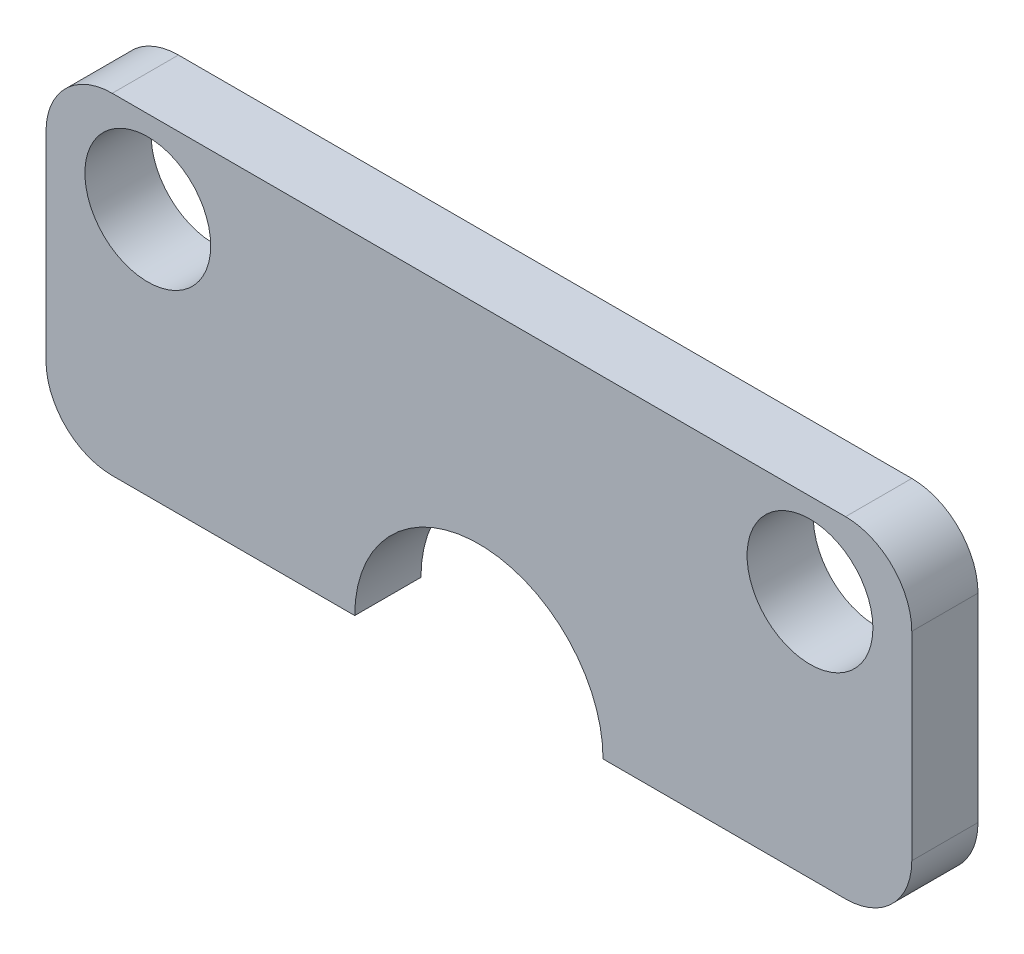
SolidWorks part; units mm, degrees
material "Plain Carbon Steel"
ref_plane "Front Plane" through (0, 0, 0) normal (0, 0, 1) x (1, 0, 0)
ref_plane "Top Plane" through (0, 0, 0) normal (0, 1, 0) x (1, 0, 0)
ref_plane "Right Plane" through (0, 0, 0) normal (1, 0, 0) x (0, 0, -1)
sketch "Sketch1" plane through (0, 0, 0) normal (0, 0, 1) x (1, 0, 0)
  line L0 (-357.1333, 162.1406) -> (-355.4516, 162.1406)
  line L1 (-357.1333, 162.1406) -> (-367.2933, 162.1406)
  line L2 (-367.2933, 162.1406) -> (-367.2933, 174.8406)
  line L4 (-334.0848, 162.1406) -> (-334.0848, 174.8406)
  line L5 (-344.2448, 162.1406) -> (-334.0848, 162.1406)
  line L6 (-367.2933, 174.8406) -> (-334.0848, 174.8406)
  line L7 (-344.2448, 162.1406) -> (-345.9266, 162.1406)
  circle A0 centre (-363.3891, 171.6656) radius 2.413
  circle A1 centre (-337.9891, 171.6656) radius 2.413
  circle A2 centre (-350.6891, 162.1406) radius 6.4443
  circle A3 centre (-350.6891, 162.1406) radius 4.7625
extrude "Boss-Extrude1" add sketch "Sketch1" along normal blind 2.54 contours A2 L5 L4 L6 L2 L1 A0 A1 | A3 L7 A2 L0
fillet "Fillet1" radius 2.54 4 edges at (-367.2933, 162.1406, 1.27) (-334.0848, 162.1406, 1.27) (-334.0848, 174.8406, 1.27) (-367.2933, 174.8406, 1.27)
